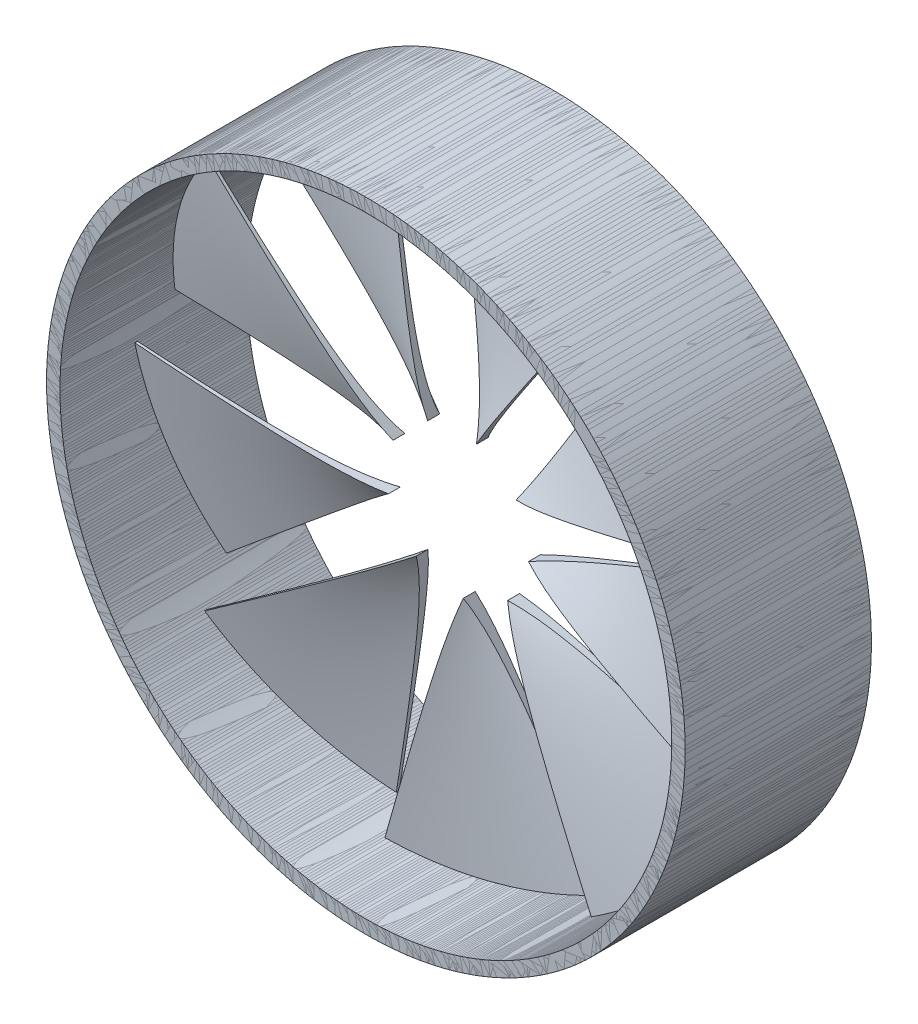
SolidWorks part; units mm, degrees
ref_plane "Front Plane" through (0, 0, 0) normal (0, 0, 1) x (1, 0, 0)
ref_plane "Top Plane" through (0, 0, 0) normal (0, 1, 0) x (1, 0, 0)
ref_plane "Right Plane" through (0, 0, 0) normal (1, 0, 0) x (0, 0, -1)
sketch "Sketch1" plane through (0, 0, 0) normal (0, 0, 1) x (1, 0, 0)
  circle A0 centre (0, 0) radius 119.994
  dimension "D1" = 239.988
curve "Helix/Spiral1" pitch 150 height 30 turns 0.2
sketch "Sketch2" plane through (0, 0, 0) normal (0, 0, 1) x (1, 0, 0)
  line L1 (-119.994, 0) -> (-25.2, 0)
  line L2 (-119.994, 0) -> (-119.994, 5)
  line L3 (-119.994, 5) -> (-25.2, 5)
  line L4 (-25.2, 0) -> (-25.2, 5)
  spline S0 degree 3 poles (-119.994, 0) (-119.994, 5.5804) (-119.213, 16.7563) (-115.721, 33.1819) (-109.9767, 48.9649) (-102.0919, 63.794) (-92.2199, 77.3817) (-80.5531, 89.4631) (-67.3177, 99.8035) (-52.775, 108.2003) (-42.3875, 112.3966) (-37.0802, 114.1211) knots 0 0 0 0 0.111111 0.222222 0.333333 0.444444 0.555556 0.666667 0.777778 0.888889 1 1 1 1 construction
  dimension "D1" = 5
  dimension "D3" = 25.2
sweep "Sweep1" add profiles "Sketch2" path "Helix/Spiral1"
ref_plane "Plane1" through (0, 0, 0) normal (0, 0, 1) x (1, 0, 0)
sketch "Sketch9" plane through (0, 0, 0) normal (0, 0, 1) x (1, 0, 0)
  line L0 (-24.2292, 11.4837) -> (-90.9717, 78.2263)
  line L1 (-24.2292, 11.4837) -> (-119.4292, 11.4837)
  arc A0 (-90.9717, 78.2263) -> (-119.4292, 11.4837) centre (0, 0) ccw
  dimension "D2" = 45
  dimension "D1" = 119.98
  dimension "D3" = 95.2
extrude "Cut-Extrude1" cut sketch "Sketch9" along normal blind 40 flip side to cut
sketch "Sketch10" plane through (0, 0, 0) normal (0, 0, 1) x (1, 0, 0)
  circle A0 centre (0, 0) radius 114.994
  circle A1 centre (0, 0) radius 119.994
  dimension "D2" = 229.988
  dimension "D1" = 5
extrude "Boss-Extrude1" add sketch "Sketch10" along normal blind 45 and the other way blind 25
pattern_circular "CirPattern2" count 9 over 360 about axis through (0, 0, -25) along (0, 0, 1) of bodies 103
equation "\"ThrusterDim\"= 140mm"
equation "\"hatchHoleDiameter\"= 600mm"
equation "\"hullThickness\"= 120mm"
equation "\"gasketHullInterconnectWidth\"= 100mm"
equation "\"collarThickness\"= 15"
equation "\"hatchTunnelLength\"=200"
equation "\"oRingDiameter\"=2"
equation "\"boltPatternRadiusInterconnect\"=500"
equation "\"interconnectBoltDiameter\"=30"
equation "\"hatchShaftDiameter\"=20"
equation "\"hatchMinima\"=50"
equation "\"hullDiameter\"=2000"
equation "\"hatchMaxima\"=180"
equation "\"bushingFlatHatch\"=15"
equation "\"hingePivotDiameter\"=20"
equation "\"handleWidth\"=250"
equation "\"handleHeight\"=160"
equation "\"handleThickness\"=25"
equation "\"FrameLength\"= 4300"
equation "\"FrameMidLength\"= 3000"
equation "\"TubeOD\"= 100"
equation "\"FrameBackFlat\"= 800"
equation "\"TubeWall\"=15"
equation "\"TopMemberAngle\"=120"
equation "\"FrameHight\"= 2500"
equation "\"D1@Sketch1\"=\"ThrusterDim\" *2 *0.8571"
equation "\"D2@Sketch10\"=\"ThrusterDim\" *2 *0.8571-10"
equation "\"th\"=16.5237"
equation "\"D3@Sketch2\"=\"ThrusterDim\" *0.18"
equation "\"D1@Sketch9\"=\"ThrusterDim\" *0.857"
equation "\"D3@Sketch9\"=\"ThrusterDim\" *0.68"
